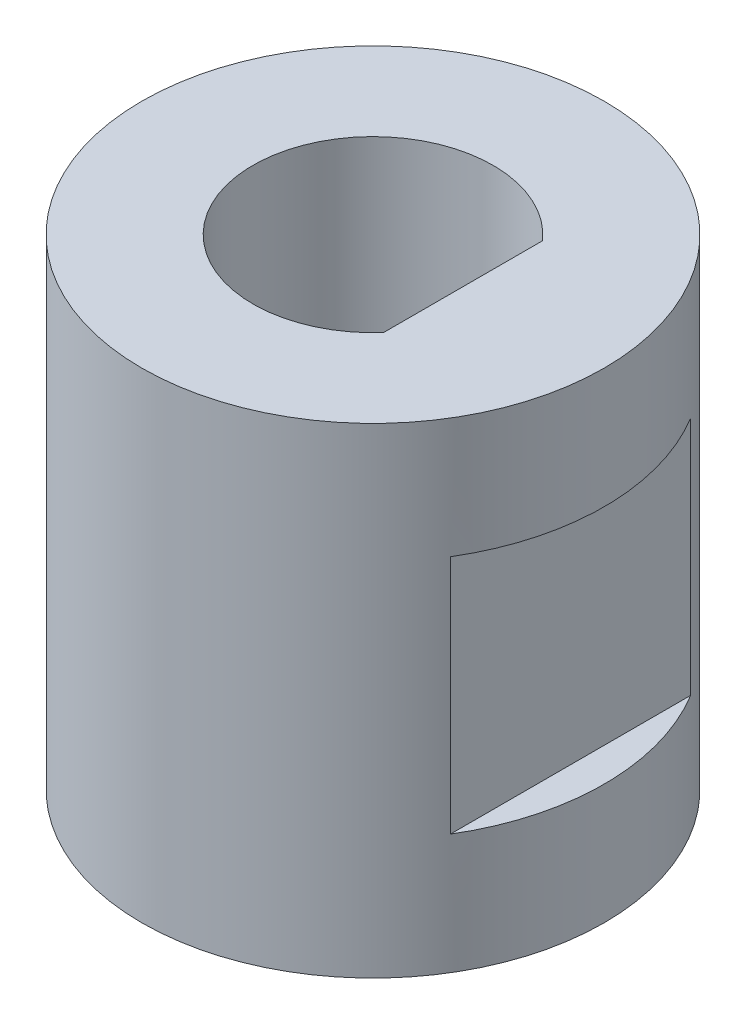
SolidWorks part; units mm, degrees
ref_plane "Front Plane" through (0, 0, 0) normal (0, 0, 1) x (1, 0, 0)
ref_plane "Top Plane" through (0, 0, 0) normal (0, 1, 0) x (1, 0, 0)
ref_plane "Right Plane" through (0, 0, 0) normal (1, 0, 0) x (0, 0, -1)
sketch "Sketch1" plane through (0, 0, 0) normal (0, 1, 0) x (1, 0, 0)
  circle A0 centre (0, 0) radius 3.85
  dimension "D1" = 7.7
extrude "Boss-Extrude1" add sketch "Sketch1" along normal blind 2 contours A0
sketch "Sketch3" plane through (0, 2, 0) normal (0, 1, 0) x (1, 0, 0)
  line L0 (3.2898, 2) -> (3.2898, -2)
  line L1 (-2, 3.2898) -> (2, 3.2898)
  arc A0 (-2, 3.2898) -> (3.2898, -2) centre (0, 0) ccw
  arc A1 (3.2898, 2) -> (2, 3.2898) centre (0, 0) ccw
  point P3 (3.2898, 2)
  point P6 (3.2898, -2)
  point P7 (-2, 3.2898)
  point P8 (2, 3.2898)
  dimension "D1" = 4
  dimension "D2" = 4
extrude "Boss-Extrude2" add sketch "Sketch3" along normal blind 4
sketch "Sketch4" plane through (0, 6, 0) normal (0, 1, 0) x (1, 0, 0)
  circle A0 centre (0, 0) radius 3.85
extrude "Boss-Extrude3" add sketch "Sketch4" along normal blind 2
sketch "Sketch5" plane through (0, 8, 0) normal (0, 1, 0) x (1, 0, 0)
  line L0 (-2, 0) -> (1.5, 0) construction
  line L1 (1.5, 1.3229) -> (1.5, -1.3229)
  arc A0 (1.5, 1.3229) -> (1.5, -1.3229) centre (0, 0) ccw
  dimension "D1" = 4
  dimension "D2" = 3.5
extrude "Cut-Extrude1" cut sketch "Sketch5" against normal through all
